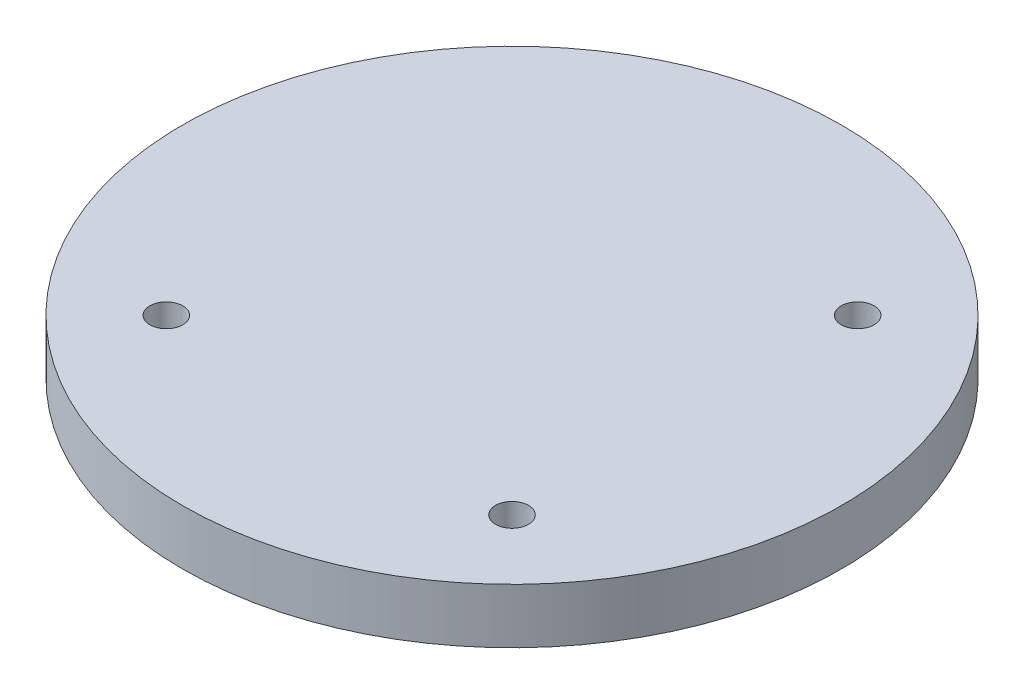
SolidWorks part; units mm, degrees
material "ABS"
ref_plane "Front Plane" through (0, 0, 0) normal (0, 0, 1) x (1, 0, 0)
ref_plane "Top Plane" through (0, 0, 0) normal (0, 1, 0) x (1, 0, 0)
ref_plane "Right Plane" through (0, 0, 0) normal (1, 0, 0) x (0, 0, -1)
sketch "Sketch1" plane through (0, 0, 0) normal (0, 1, 0) x (1, 0, 0)
  line L0 (0, 0) -> (0, 44.0979) construction
  line L1 (2.4064, 0) -> (50002.4064, 0) construction
  line L2 (0, 0) -> (43.9838, 43.9838) construction
  circle A0 centre (0, 0) radius 30
  circle A1 centre (0, 0) radius 22.25 construction
  point P10 (15.7331, 15.7331)
  point P11 (-15.7331, -15.7331)
  dimension "D1" = 60
  dimension "D3" = 44.5
  dimension "D2" = 45
extrude "Boss-Extrude1" add sketch "Sketch1" along normal blind 5
sketch "Sketch4" plane through (0, 5, 0) normal (0, 1, 0) x (1, 0, 0)
  line L0 (0, 0) -> (0, 31.7542) construction
  line L1 (0, 0) -> (39.9812, 0) construction
  line L2 (0, 0) -> (25.2582, 25.2582) construction
  line L3 (0, 0) -> (-28.102, 28.102) construction
  circle A0 centre (0, 0) radius 22.25 construction
  point P2 (-15.7331, -15.7331)
  point P5 (15.7331, -15.7331)
  point P12 (15.7331, 15.7331)
  dimension "D2" = 44.5
  dimension "D1" = 45
hole_wizard "Ø3.0 (3) Diameter Hole1" positions "Sketch6" profile "Sketch5" hole size "Ø3.0" standard "ANSI Metric" end condition up to next
sketch "Sketch6" plane through (0, 5, 0) normal (0, 1, 0) x (1, 0, 0)
  point P0 (-15.7331, -15.7331)
  point P3 (15.7331, -15.7331)
  point P6 (15.7331, 15.7331)
sketch "Sketch5" plane through (-15.7331, 5, 15.7331) normal (1, 0, 0) x (0, 0, 1)
  line L0 (0, 0) -> (0, 5)
  line L1 (0, 5) -> (1.5, 5)
  line L2 (1.5, 5) -> (1.5, 0)
  line L5 (1.5, 0) -> (0, 0)
  line L11 (0, -6.35) -> (0, 107.95) construction
  dimension "Thru Hole Dia." = 3
  dimension "Thru Hole Depth" = 5
